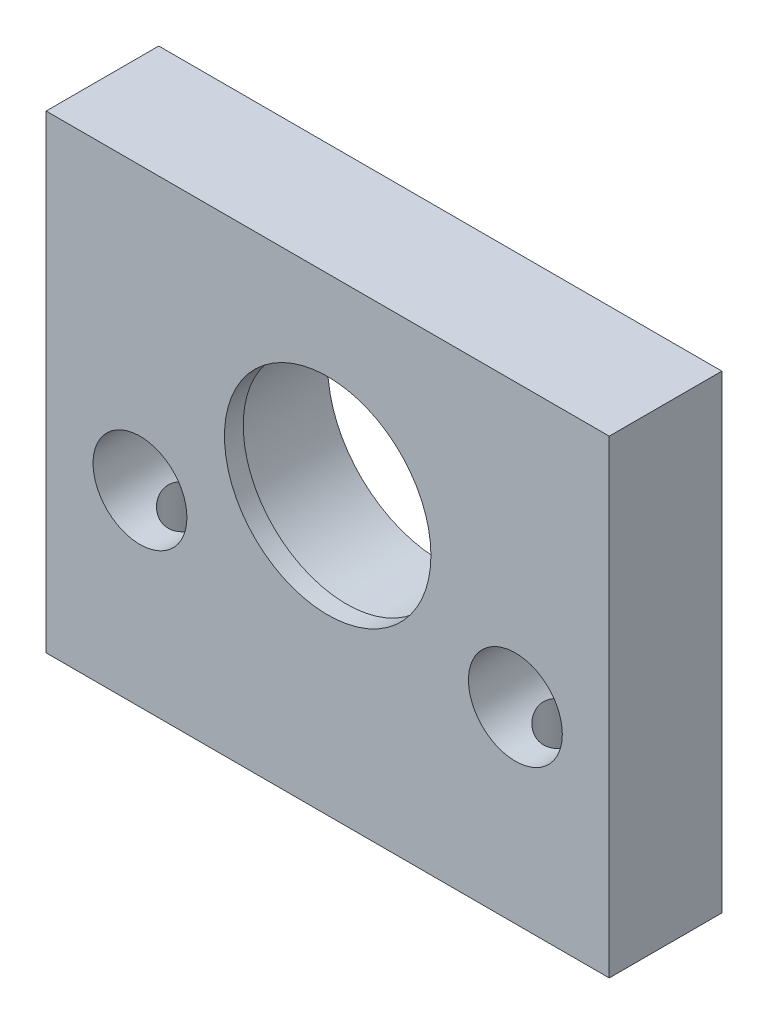
SolidWorks part; units mm, degrees
material "Beech"
ref_plane "Front Plane" through (0, 0, 0) normal (0, 0, 1) x (1, 0, 0)
ref_plane "Top Plane" through (0, 0, 0) normal (0, 1, 0) x (1, 0, 0)
ref_plane "Right Plane" through (0, 0, 0) normal (1, 0, 0) x (0, 0, -1)
sketch "Sketch1" plane through (0, 0, 0) normal (0, 0, 1) x (1, 0, 0)
  line L1 (-30, 25) -> (30, 25)
  line L2 (-30, 25) -> (-30, -25)
  line L3 (-30, -25) -> (30, -25)
  line L4 (30, 25) -> (30, -25)
  line L5 (-30, 25) -> (30, -25) construction
  line L6 (-30, -25) -> (30, 25) construction
  point P0 (0, 0)
  dimension "D1" = 60
  dimension "D2" = 50
extrude "Boss-Extrude1" add sketch "Sketch1" along normal blind 12
sketch "Sketch2" plane through (0, 0, 12) normal (0, 0, 1) x (1, 0, 0)
  line L3 (-30, -25) -> (30, -25) construction
  circle A0 centre (0, 4.5) radius 11
  dimension "D1" = 22
  dimension "D2" = 29.5
extrude "Cut-Extrude1" cut sketch "Sketch2" against normal blind 2
sketch "Sketch3" plane through (0, 0, 12) normal (0, 0, 1) x (1, 0, 0)
  line L0 (-30, -25) -> (30, -25) construction
  line L1 (-30, 25) -> (-30, -25) construction
  line L2 (30, -25) -> (30, 25) construction
  circle A0 centre (-20, -5) radius 5
  circle A1 centre (20, -5) radius 5
  dimension "D1" = 10
  dimension "D2" = 10
  dimension "D5" = 20
  dimension "D6" = 10
  dimension "D3" = 20
  dimension "D4" = 10
extrude "Cut-Extrude2" cut sketch "Sketch3" against normal up to next
sketch "Sketch4" plane through (0, -25, 0) normal (0, -1, 0) x (1, 0, 0)
  line L0 (28.9668, 6) -> (-28.5117, 6) construction
  line L1 (30, 12) -> (30, 0) construction
  line L2 (-30, 12) -> (-30, 0) construction
  circle A0 centre (20, 6) radius 3
  circle A1 centre (-20, 6) radius 3
  dimension "D1" = 6
  dimension "D2" = 6
  dimension "D3" = 10
  dimension "D4" = 10
extrude "Cut-Extrude3" cut sketch "Sketch4" against normal up to next
sketch "Sketch6" plane through (0, 0, 10) normal (0, 0, 1) x (1, 0, 0)
  circle A0 centre (0, 4.5) radius 12
  dimension "D1" = 24
extrude "Cut-Extrude5" cut sketch "Sketch6" against normal up to next
